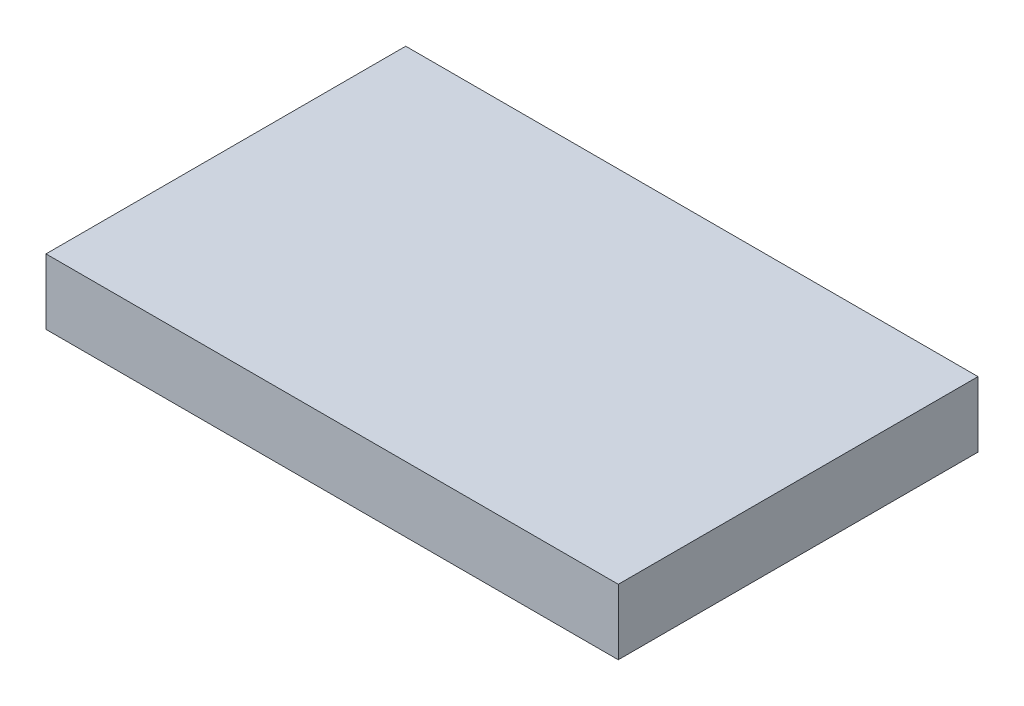
SolidWorks part; units mm, degrees
ref_plane "Front Plane" through (0, 0, 0) normal (0, 0, 1) x (1, 0, 0)
ref_plane "Top Plane" through (0, 0, 0) normal (0, 1, 0) x (1, 0, 0)
ref_plane "Right Plane" through (0, 0, 0) normal (1, 0, 0) x (0, 0, -1)
sketch "Sketch1" plane through (0, 0, 0) normal (0, 1, 0) x (1, 0, 0)
  line L1 (0, 0) -> (55.5625, 0)
  line L2 (0, 0) -> (0, 34.925)
  line L3 (0, 34.925) -> (55.5625, 34.925)
  line L4 (55.5625, 0) -> (55.5625, 34.925)
  dimension "D1" = 34.925
  dimension "D2" = 55.5625
extrude "Boss-Extrude1" add sketch "Sketch1" along normal blind 6.35
